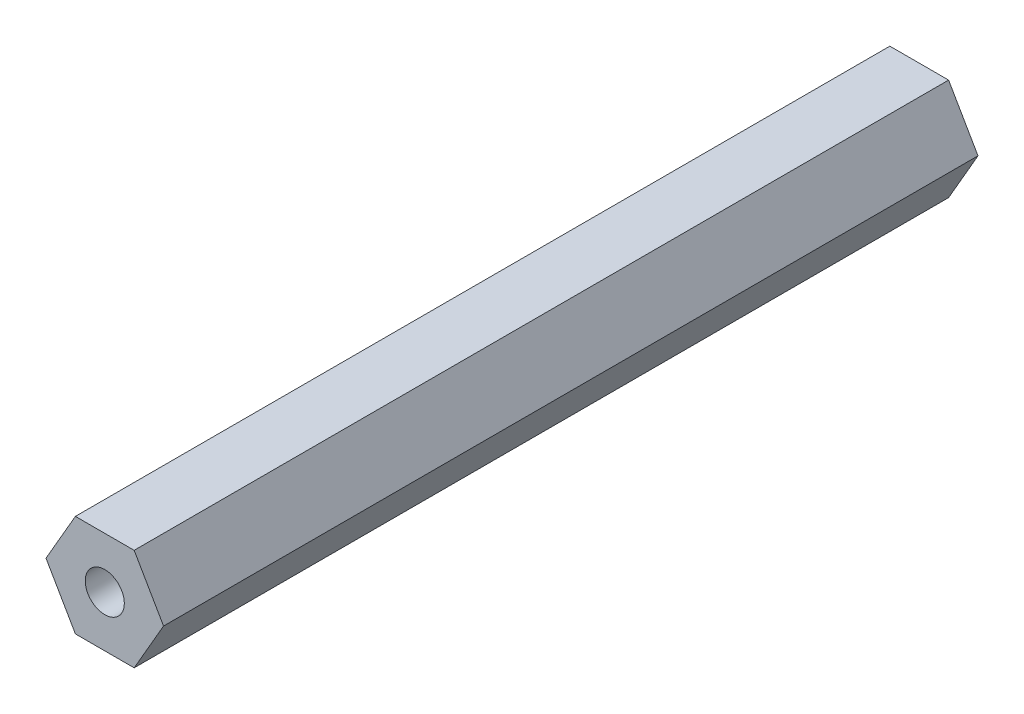
SolidWorks part; units mm, degrees
ref_plane "Front Plane" through (0, 0, 0) normal (0, 0, 1) x (1, 0, 0)
ref_plane "Top Plane" through (0, 0, 0) normal (0, 1, 0) x (1, 0, 0)
ref_plane "Right Plane" through (0, 0, 0) normal (1, 0, 0) x (0, 0, -1)
sketch "Sketch1" plane through (0, 0, 0) normal (0, 0, 1) x (1, 0, 0)
  line L1 (-117.8707, 0) -> (-120.162, 3.9688)
  line L2 (-120.162, 3.9688) -> (-124.7448, 3.9687)
  line L3 (-124.7448, 3.9687) -> (-127.0361, 0)
  line L4 (-127.0361, 0) -> (-124.7448, -3.9688)
  line L5 (-124.7448, -3.9688) -> (-120.162, -3.9687)
  line L6 (-120.162, -3.9687) -> (-117.8707, 0)
  circle A0 centre (-122.4534, 0) radius 3.9687 construction
  point P1 (-122.4534, -3.9688)
  dimension "D1" = 7.9375
extrude "Boss-Extrude1" add sketch "Sketch1" along normal blind 63.5
sketch "Sketch2" plane through (0, 0, 63.5) normal (0, 0, 1) x (1, 0, 0)
  circle A0 centre (-122.4534, 0) radius 1.524
  dimension "D1" = 3.048
extrude "Cut-Extrude1" cut sketch "Sketch2" against normal blind 19.05
sketch "Sketch3" plane through (0, 0, 0) normal (0, 0, -1) x (-1, 0, 0)
  line L0 (120.162, 3.9688) -> (124.7448, -3.9688)
  circle A0 centre (122.4534, 0) radius 1.524
  dimension "D1" = 3.048
extrude "Cut-Extrude2" cut sketch "Sketch3" against normal blind 19.05 contours A0
sketch "Sketch6" plane through (0, -3.9687, 0) normal (0, -1, 0) x (1, 0, 0)
  line L0 (-124.7448, 4.33) -> (-124.7448, 5.83)
  line L1 (-124.7448, 4.33) -> (-127.0361, 4.33)
  line L2 (-124.7448, 5.83) -> (-127.0361, 5.83)
  line L3 (-127.0361, 4.33) -> (-127.0361, 5.83)
  line L4 (-124.7448, 63.5) -> (-124.7448, 0) construction
  line L5 (-127.0361, 63.5) -> (-127.0361, 0) construction
  line L6 (128.5748, 0) -> (-128.5748, 0) construction
  line L7 (-124.7448, 9.41) -> (-124.7448, 10.91)
  line L8 (-124.7448, 9.41) -> (-127.0361, 9.41)
  line L9 (-127.0361, 9.41) -> (-127.0361, 10.91)
  line L10 (-124.7448, 10.91) -> (-127.0361, 10.91)
  line L11 (-124.7448, 14.49) -> (-124.7448, 15.99)
  line L12 (-124.7448, 14.49) -> (-127.0361, 14.49)
  line L13 (-127.0361, 14.49) -> (-127.0361, 15.99)
  line L14 (-124.7448, 15.99) -> (-127.0361, 15.99)
  line L15 (-124.7448, 19.57) -> (-124.7448, 21.07)
  line L16 (-124.7448, 19.57) -> (-127.0361, 19.57)
  line L17 (-127.0361, 19.57) -> (-127.0361, 21.07)
  line L18 (-124.7448, 21.07) -> (-127.0361, 21.07)
  line L19 (-124.7448, 24.65) -> (-124.7448, 26.15)
  line L20 (-124.7448, 24.65) -> (-127.0361, 24.65)
  line L21 (-127.0361, 24.65) -> (-127.0361, 26.15)
  line L22 (-124.7448, 26.15) -> (-127.0361, 26.15)
  line L23 (-124.7448, 29.73) -> (-124.7448, 31.23)
  line L24 (-124.7448, 29.73) -> (-127.0361, 29.73)
  line L25 (-127.0361, 29.73) -> (-127.0361, 31.23)
  line L26 (-124.7448, 31.23) -> (-127.0361, 31.23)
  line L27 (-124.7448, 34.81) -> (-124.7448, 36.31)
  line L28 (-124.7448, 34.81) -> (-127.0361, 34.81)
  line L29 (-127.0361, 34.81) -> (-127.0361, 36.31)
  line L30 (-124.7448, 36.31) -> (-127.0361, 36.31)
  line L31 (-124.7448, 39.89) -> (-124.7448, 41.39)
  line L32 (-124.7448, 39.89) -> (-127.0361, 39.89)
  line L33 (-127.0361, 39.89) -> (-127.0361, 41.39)
  line L34 (-124.7448, 41.39) -> (-127.0361, 41.39)
  line L35 (-124.7448, 44.97) -> (-124.7448, 46.47)
  line L36 (-124.7448, 44.97) -> (-127.0361, 44.97)
  line L37 (-127.0361, 44.97) -> (-127.0361, 46.47)
  line L38 (-124.7448, 46.47) -> (-127.0361, 46.47)
  line L39 (-124.7448, 50.05) -> (-124.7448, 51.55)
  line L40 (-124.7448, 50.05) -> (-127.0361, 50.05)
  line L41 (-127.0361, 50.05) -> (-127.0361, 51.55)
  line L42 (-124.7448, 51.55) -> (-127.0361, 51.55)
  line L43 (-124.7448, 55.13) -> (-124.7448, 56.63)
  line L44 (-124.7448, 55.13) -> (-127.0361, 55.13)
  line L45 (-127.0361, 55.13) -> (-127.0361, 56.63)
  line L46 (-124.7448, 56.63) -> (-127.0361, 56.63)
  line L47 (-124.7448, 60.21) -> (-124.7448, 61.71)
  line L48 (-124.7448, 60.21) -> (-127.0361, 60.21)
  line L49 (-127.0361, 60.21) -> (-127.0361, 61.71)
  line L50 (-124.7448, 61.71) -> (-127.0361, 61.71)
  line L51 (-124.7448, 65.29) -> (-124.7448, 66.79)
  line L52 (-124.7448, 65.29) -> (-127.0361, 65.29)
  line L53 (-127.0361, 65.29) -> (-127.0361, 66.79)
  line L54 (-124.7448, 66.79) -> (-127.0361, 66.79)
  line L55 (-124.7448, 70.37) -> (-124.7448, 71.87)
  line L56 (-124.7448, 70.37) -> (-127.0361, 70.37)
  line L57 (-127.0361, 70.37) -> (-127.0361, 71.87)
  line L58 (-124.7448, 71.87) -> (-127.0361, 71.87)
  dimension "D1" = 1.5
  dimension "D2" = 4.33
extrude "Cut-Extrude4" cut sketch "Sketch6" against normal blind 19.05
